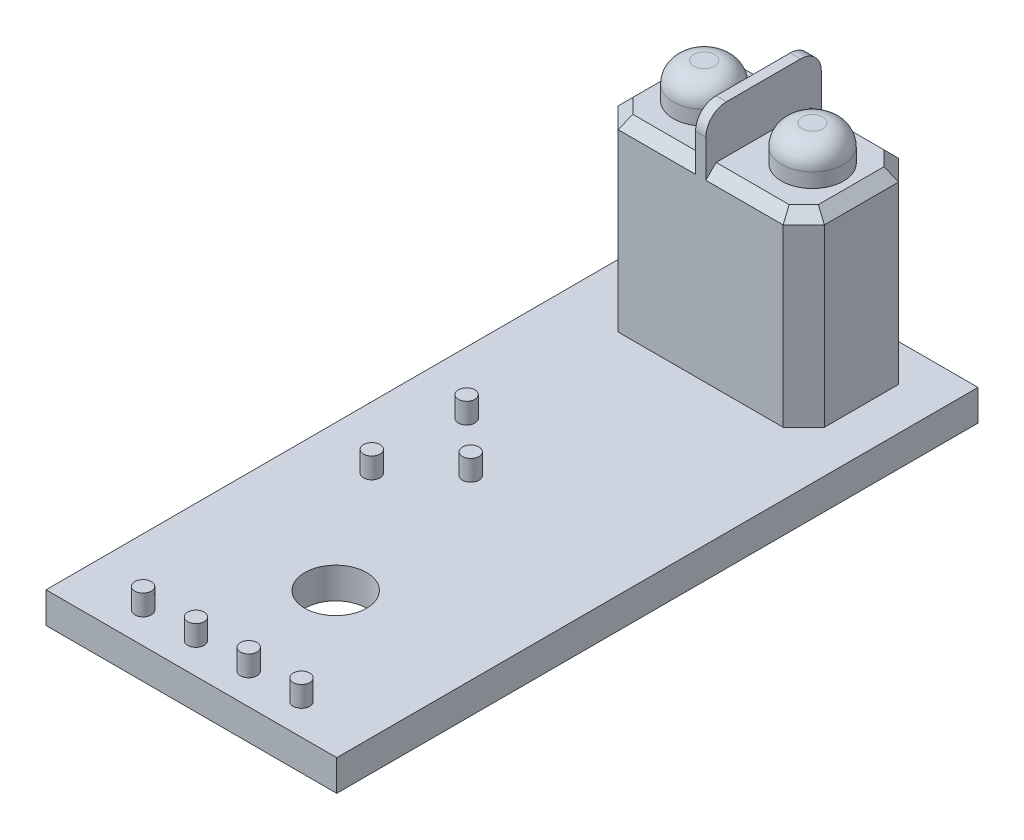
SolidWorks part; units mm, degrees
ref_plane "Front Plane" through (0, 0, 0) normal (0, 0, 1) x (1, 0, 0)
ref_plane "Top Plane" through (0, 0, 0) normal (0, 1, 0) x (1, 0, 0)
ref_plane "Right Plane" through (0, 0, 0) normal (1, 0, 0) x (0, 0, -1)
sketch "Sketch1" plane through (0, 0, 0) normal (0, 1, 0) x (1, 0, 0)
  line L1 (-7.05, 15.55) -> (7.05, 15.55)
  line L2 (-7.05, 15.55) -> (-7.05, -15.55)
  line L3 (-7.05, -15.55) -> (7.05, -15.55)
  line L4 (7.05, 15.55) -> (7.05, -15.55)
  line L5 (-7.05, 15.55) -> (7.05, -15.55) construction
  line L6 (-7.05, -15.55) -> (7.05, 15.55) construction
  point P0 (0, 0)
  dimension "D1" = 14.1
  dimension "D2" = 31.1
extrude "Boss-Extrude1" add sketch "Sketch1" along normal blind 1.5
sketch "Sketch2" plane through (0, 1.5, 0) normal (0, 1, 0) x (1, 0, 0)
  line L0 (0, 15.55) -> (0, -15.55) construction
  line L1 (7.05, 15.55) -> (-7.05, 15.55) construction
  line L2 (-7.05, -15.55) -> (7.05, -15.55) construction
  line L4 (-5, 14.75) -> (5, 14.75)
  line L5 (-5, 14.75) -> (-5, 9.15)
  line L6 (-5, 9.15) -> (5, 9.15)
  line L7 (5, 14.75) -> (5, 9.15)
  line L8 (-5, 14.75) -> (5, 9.15) construction
  line L9 (-5, 9.15) -> (5, 14.75) construction
  point P6 (0, 11.95)
  dimension "D1" = 10
  dimension "D2" = 5.6
  dimension "D3" = 0.8
extrude "Boss-Extrude2" add sketch "Sketch2" along normal blind 9
sketch "Sketch3" plane through (0, 10.5, 0) normal (0, 1, 0) x (1, 0, 0)
  line L0 (0, 14.75) -> (0, 9.15) construction
  line L1 (5, 14.75) -> (-5, 14.75) construction
  line L2 (-5, 9.15) -> (5, 9.15) construction
  line L3 (-5, 9.15) -> (5, 9.15) construction
  line L4 (-0.25, 14.75) -> (0.25, 14.75)
  line L5 (-0.25, 14.75) -> (-0.25, 9.15)
  line L6 (-0.25, 9.15) -> (0.25, 9.15)
  line L7 (0.25, 14.75) -> (0.25, 9.15)
  line L8 (-0.25, 14.75) -> (0.25, 9.15) construction
  line L9 (-0.25, 9.15) -> (0.25, 14.75) construction
  point P6 (0, 11.95)
  dimension "D1" = 0.5
extrude "Boss-Extrude3" add sketch "Sketch3" along normal blind 2.3
sketch "Sketch4" plane through (0, 10.5, 0) normal (0, 1, 0) x (1, 0, 0)
  line L0 (-0.25, 11.95) -> (-5, 11.95) construction
  line L1 (-0.25, 14.75) -> (-0.25, 9.15) construction
  line L2 (-5, 14.75) -> (-5, 9.15) construction
  line L3 (0.25, 11.95) -> (5, 11.95) construction
  line L4 (0.25, 9.15) -> (0.25, 14.75) construction
  line L5 (5, 9.15) -> (5, 14.75) construction
  circle A0 centre (-2.625, 11.95) radius 1.5
  circle A1 centre (2.625, 11.95) radius 1.5
  dimension "D1" = 3
  dimension "D2" = 3
extrude "Boss-Extrude4" add sketch "Sketch4" along normal blind 1.7
chamfer "Chamfer1" distance 1 angle 45 4 edges at (-5, 6, -14.75) (-5, 6, -9.15) (5, 6, -9.15) (5, 6, -14.75)
chamfer "Chamfer2" distance 0.5 angle 45 10 edges at (2.125, 10.5, -14.75) (4.5, 10.5, -14.25) (5, 10.5, -11.95) (4.5, 10.5, -9.65) (2.125, 10.5, -9.15) (-2.125, 10.5, -14.75) (-4.5, 10.5, -14.25) (-5, 10.5, -11.95) (-2.125, 10.5, -9.15) (-4.5, 10.5, -9.65)
fillet "Fillet1" radius 1 2 edges at (-2.625, 12.2, -10.45) (2.625, 12.2, -10.45)
fillet "Fillet2" radius 1 2 edges at (0, 12.8, -9.15) (0, 12.8, -14.75)
sketch "Sketch5" plane through (0, 1.5, 0) normal (0, 1, 0) x (1, 0, 0)
  line L0 (-4.05, 1.85) -> (-1.55, -0.45) construction
  line L1 (-1.55, -0.45) -> (-4.05, -2.75) construction
  line L2 (-4.05, -2.75) -> (-4.05, 1.85) construction
  line L4 (-4.05, -0.45) -> (-1.55, -0.45) construction
  line L6 (-7.05, 15.55) -> (-7.05, -15.55) construction
  line L7 (-7.05, -15.55) -> (7.05, -15.55) construction
  line L8 (0, -15.55) -> (0, 15.55) construction
  line L9 (7.05, 15.55) -> (-7.05, 15.55) construction
  circle A0 centre (-4.05, 1.85) radius 0.4
  circle A1 centre (-1.55, -0.45) radius 0.4
  circle A2 centre (-4.05, -2.75) radius 0.4
  circle A3 centre (1.9279, -6.8733) radius 1.4
  circle A4 centre (-3.84, -14.05) radius 0.4
  circle A5 centre (-1.28, -14.05) radius 0.4
  circle A6 centre (1.28, -14.05) radius 0.4
  circle A7 centre (3.84, -14.05) radius 0.4
  dimension "D1" = 0.8
  dimension "D2" = 0.8
  dimension "D3" = 0.8
  dimension "D4" = 0.8
  dimension "D5" = 0.8
  dimension "D6" = 0.8
  dimension "D7" = 0.8
  dimension "D8" = 2.8
  dimension "D9" = 0
  dimension "D10" = 90
  dimension "D11" = 2.5
  dimension "D12" = 3
  dimension "D13" = 12.8
  dimension "D14" = 4.6
  dimension "D15" = 2.56
  dimension "D16" = 2.56
  dimension "D17" = 2.56
  dimension "D18" = 1.28
  dimension "D19" = 1.5
  dimension "D20" = 1.5
  dimension "D21" = 1.5
  dimension "D22" = 1.5
extrude "Boss-Extrude5" add sketch "Sketch5" along normal blind 1 contours A4 | A5 | A6 | A7 | A2 | A1 | A0
sketch "Sketch6" plane through (0, 1.5, 0) normal (0, 1, 0) x (1, 0, 0)
  line L0 (0, -15.55) -> (0, 15.55) construction
  line L1 (-7.05, -15.55) -> (7.05, -15.55) construction
  line L2 (7.05, 15.55) -> (-7.05, 15.55) construction
  line L3 (0, -15.55) -> (0, -10.05) construction
  line L5 (0, -8.55) -> (1.5, -8.55) construction
  line L6 (0, -8.55) -> (-1.5, -8.55) construction
  circle A0 centre (0, -8.55) radius 1.5
  dimension "D2" = 1.5
  dimension "D3" = 3
  dimension "D1" = 5.5
extrude "Cut-Extrude1" cut sketch "Sketch6" against normal blind 11
